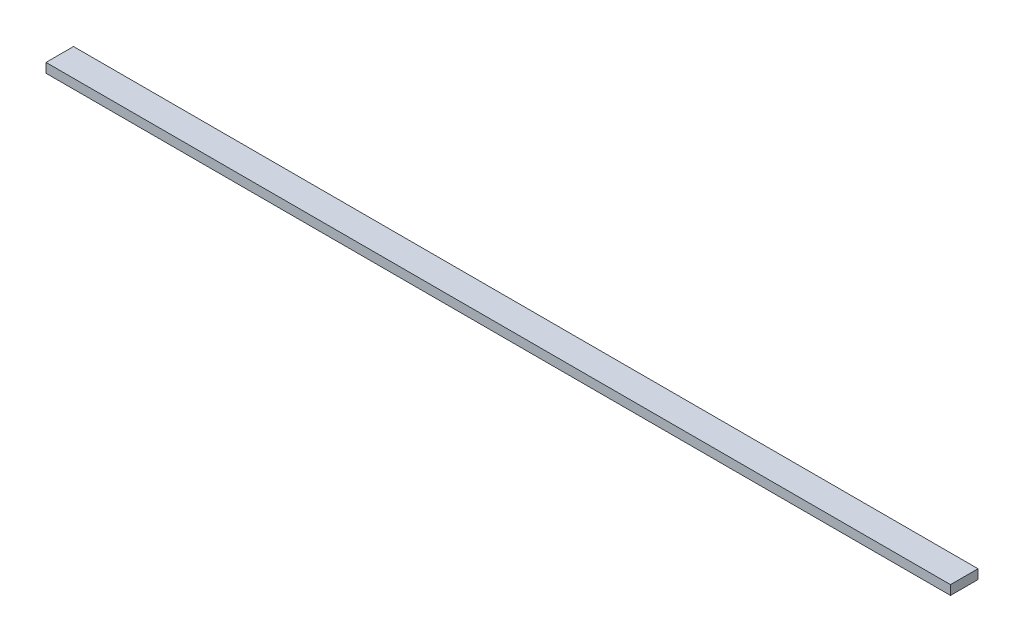
SolidWorks part; units mm, degrees
ref_plane "Front Plane" through (0, 0, 0) normal (0, 0, 1) x (1, 0, 0)
ref_plane "Top Plane" through (0, 0, 0) normal (0, 1, 0) x (1, 0, 0)
ref_plane "Right Plane" through (0, 0, 0) normal (1, 0, 0) x (0, 0, -1)
sketch "Sketch1" plane through (0, 0, 0) normal (0, 1, 0) x (1, 0, 0)
  line L1 (-304.8, -9.271) -> (304.8, -9.271)
  line L2 (-304.8, -9.271) -> (-304.8, 9.271)
  line L3 (-304.8, 9.271) -> (304.8, 9.271)
  line L4 (304.8, -9.271) -> (304.8, 9.271)
  line L5 (-304.8, -9.271) -> (304.8, 9.271) construction
  line L6 (-304.8, 9.271) -> (304.8, -9.271) construction
  point P0 (0, 0)
  dimension "D1" = 18.542
  dimension "D2" = 609.6
extrude "Boss-Extrude1" add sketch "Sketch1" along normal blind 6.35
